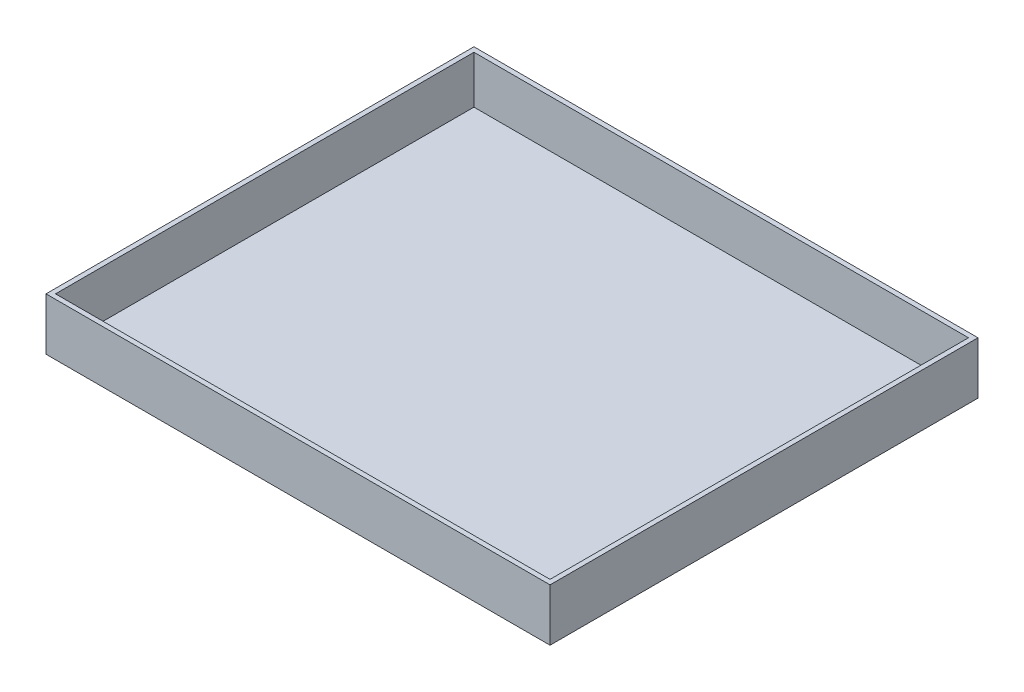
SolidWorks part; units mm, degrees
ref_plane "Alzado" through (0, 0, 0) normal (0, 0, 1) x (1, 0, 0)
ref_plane "Planta" through (0, 0, 0) normal (0, 1, 0) x (1, 0, 0)
ref_plane "Vista lateral" through (0, 0, 0) normal (1, 0, 0) x (0, 0, -1)
sketch "Croquis1" plane through (0, 0, 0) normal (0, 1, 0) x (1, 0, 0)
  line L1 (265, -225) -> (-265, -225)
  line L2 (265, -225) -> (265, 225)
  line L3 (265, 225) -> (-265, 225)
  line L4 (-265, -225) -> (-265, 225)
  line L5 (265, -225) -> (-265, 225) construction
  line L6 (265, 225) -> (-265, -225) construction
  point P0 (0, 0)
  dimension "D1" = 530
  dimension "D2" = 450
extrude "Extruir-Lámina1" add sketch "Croquis1" against normal blind 50 thin
sketch "Croquis2" plane through (0, -50, 0) normal (0, -1, 0) x (1, 0, 0)
  line L4 (-265, 225) -> (-265, -225)
  line L5 (-265, -225) -> (265, -225)
  line L6 (265, -225) -> (265, 225)
  line L7 (265, 225) -> (-265, 225)
  line L8 (-265, 225) -> (-265, -225)
  line L9 (-265, -225) -> (265, -225)
  line L10 (265, -225) -> (265, 225)
  line L11 (265, 225) -> (-265, 225)
  dimension "D1" = 0
extrude "Extruir1" add sketch "Croquis2" along normal blind 5
